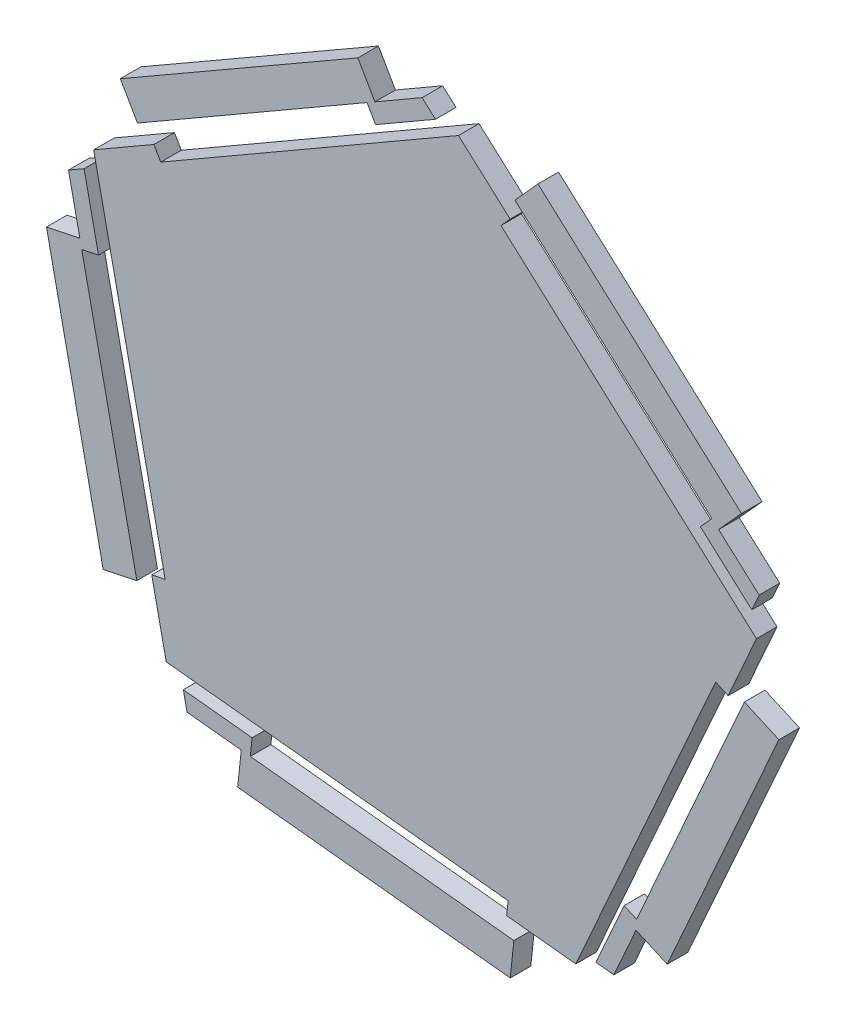
SolidWorks part; units mm, degrees
ref_plane "Front Plane" through (0, 0, 0) normal (0, 0, 1) x (1, 0, 0)
ref_plane "Top Plane" through (0, 0, 0) normal (0, 1, 0) x (1, 0, 0)
ref_plane "Right Plane" through (0, 0, 0) normal (1, 0, 0) x (0, 0, -1)
sketch "Sketch1" plane through (0, 0, 0) normal (0, 0, 1) x (1, 0, 0)
  line L1 (-41.404, -45.8843) -> (30.844, -53.5566)
  line L2 (30.844, -53.5566) -> (60.4667, 12.7845)
  line L3 (60.4667, 12.7845) -> (6.5264, 61.4578)
  line L4 (6.5264, 61.4578) -> (-56.4331, 25.1985)
  line L5 (-56.4331, 25.1985) -> (-41.404, -45.8843)
  circle A0 centre (0, 0) radius 50 construction
extrude "Boss-Extrude1" add sketch "Sketch1" along normal blind 3 contours L4 L5 L1 L2 L3
sketch "Sketch4" plane through (0, 0, 3) normal (0, 0, 1) x (1, 0, 0)
  line L0 (14.0812, -44.2141) -> (14.2946, -42.2255)
  line L1 (49.2224, -0.0815) -> (48.7656, 0.1219)
  line L3 (-39.7738, 28.9981) -> (-6.2904, 48.3298)
  line L4 (-47.56, 19.3386) -> (-49.8378, 18.0301)
  line L5 (-23.3185, -42.797) -> (15.1331, -46.8384)
  line L6 (1.747, 52.9701) -> (-5.1421, 48.9927)
  line L7 (5.2171, 49.1278) -> (5.2906, 49.8199) construction
  line L8 (49.8438, 12.3098) -> (50.9174, 14.7072)
  line L9 (44.0205, 20.9172) -> (15.288, 46.7881)
  line L10 (46.4014, -0.2709) -> (44.5761, 0.5466)
  line L12 (29.7217, -43.8806) -> (32.9573, -36.6135)
  line L22 (-41.404, -45.8843) -> (30.844, -53.5566) construction
  line L23 (14.6082, -51.8324) -> (15.1331, -46.8384)
  line L25 (37.5009, -38.6482) -> (32.9573, -36.6135)
  line L26 (37.5009, -38.6482) -> (30.844, -53.5566)
  line L27 (30.844, -53.5566) -> (14.6082, -51.8324)
  line L28 (-44.7814, -29.9103) -> (-39.8696, -28.8663)
  line L29 (-25.1682, -47.6084) -> (-24.6325, -42.6156)
  line L30 (-25.1682, -47.6084) -> (-41.404, -45.8843)
  line L31 (-41.404, -45.8843) -> (-44.7814, -29.9103)
  line L32 (-37.6988, -27.055) -> (-35.7416, -26.6434)
  line L33 (-42.2846, 33.3468) -> (-39.7738, 28.9981)
  line L34 (-53.0557, 9.2245) -> (-48.1417, 10.258)
  line L35 (-53.0557, 9.2245) -> (-56.4331, 25.1985)
  line L36 (-56.4331, 25.1985) -> (-42.2846, 33.3468)
  line L37 (-37.3804, 27.4932) -> (-36.3841, 25.759)
  line L38 (18.6481, 50.5198) -> (15.288, 46.7881)
  line L39 (-7.6221, 53.3095) -> (-5.1207, 48.9553)
  line L40 (-7.6221, 53.3095) -> (6.5264, 61.4578)
  line L41 (6.5264, 61.4578) -> (18.6481, 50.5198)
  line L42 (14.5964, 44.0467) -> (13.255, 42.5633)
  line L43 (53.8097, -2.1239) -> (49.2224, -0.0815)
  line L44 (48.345, 23.7226) -> (45.0058, 20.03)
  line L45 (48.345, 23.7226) -> (60.4667, 12.7845)
  line L46 (60.4667, 12.7845) -> (53.8097, -2.1239)
  line L50 (-44.7814, -29.9103) -> (-39.8696, -28.8663)
  line L51 (-41.404, -45.8843) -> (-44.7814, -29.9103)
  line L52 (-25.1682, -47.6084) -> (-41.404, -45.8843)
  line L53 (-25.1682, -47.6084) -> (-24.6325, -42.6156)
  line L54 (-24.6325, -42.6156) -> (-32.5518, -41.8105)
  line L56 (-42.2846, 33.3468) -> (-39.7738, 28.9981)
  line L57 (-56.4331, 25.1985) -> (-42.2846, 33.3468)
  line L58 (-53.0557, 9.2245) -> (-56.4331, 25.1985)
  line L59 (-53.0557, 9.2245) -> (-48.1417, 10.258)
  line L60 (-48.1417, 10.258) -> (-49.8232, 18.0385)
  line L62 (18.6481, 50.5198) -> (15.288, 46.7881)
  line L63 (6.5264, 61.4578) -> (18.6481, 50.5198)
  line L64 (-7.6221, 53.3095) -> (6.5264, 61.4578)
  line L65 (-7.6221, 53.3095) -> (-5.1207, 48.9553)
  line L66 (-5.1207, 48.9553) -> (1.7594, 52.9589)
  line L68 (53.8097, -2.1239) -> (49.2224, -0.0815)
  line L69 (60.4667, 12.7845) -> (53.8097, -2.1239)
  line L70 (48.345, 23.7226) -> (60.4667, 12.7845)
  line L71 (48.345, 23.7226) -> (45.0058, 20.03)
  line L73 (33.0398, -35.1989) -> (31.2127, -34.3854)
  line L75 (31.2127, -34.3854) -> (27.1099, -43.6004)
  line L76 (46.4014, -0.2709) -> (50.5296, 9.0011)
  line L78 (33.0398, -35.1989) -> (48.7656, 0.1219)
  line L80 (44.5761, 0.5466) -> (24.175, -45.275)
  line L81 (-23.0572, -40.3107) -> (-33.089, -39.2563)
  line L82 (-33.089, -39.2563) -> (-32.5484, -41.8269)
  line L83 (14.2946, -42.2255) -> (-35.5886, -36.9826)
  line L84 (14.0812, -44.2141) -> (24.175, -45.275)
  line L85 (-37.6988, -27.055) -> (-35.5886, -36.9826)
  line L87 (13.8103, -46.7398) -> (13.8146, -46.6998)
  line L88 (-23.3185, -42.797) -> (-23.0572, -40.3107)
  line L89 (-45.4628, 9.472) -> (-47.56, 19.3386)
  line L90 (-47.9082, 8.9522) -> (-39.8696, -28.8663)
  line L91 (-35.7416, -26.6434) -> (-46.17, 22.4185)
  line L92 (-37.3804, 27.4932) -> (-46.17, 22.4185)
  line L93 (3.6953, 51.2082) -> (1.747, 52.9701)
  line L95 (-40.1846, -27.5777) -> (-40.1453, -27.5695)
  line L96 (-47.9082, 8.9522) -> (-45.4628, 9.472)
  line L97 (-5.0404, 46.1647) -> (3.6953, 51.2082)
  line L98 (14.5964, 44.0467) -> (7.054, 50.838)
  line L99 (-36.3841, 25.759) -> (7.054, 50.838)
  line L104 (-6.2904, 48.3298) -> (-5.0404, 46.1647)
  line L105 (42.3477, 19.0594) -> (49.8438, 12.3098)
  line L107 (13.255, 42.5633) -> (50.5296, 9.0011)
  line L111 (16.3002, 45.9308) -> (16.2733, 45.901)
  line L112 (44.0205, 20.9172) -> (42.3477, 19.0594)
  line L113 (27.1099, -43.6004) -> (29.7217, -43.8806)
  line L114 (-45.7012, 20.4065) -> (-45.7466, 20.4268) construction
  line L121 (-49.8378, 18.0301) -> (-48.1838, 10.2491)
  line L124 (50.9174, 14.7072) -> (45.0058, 20.03)
  line L131 (-23.2663, -42.2997) -> (13.8679, -46.2027) [skipped]
  line L133 (-32.5484, -41.8269) -> (-24.6371, -42.6584)
  line L136 (-47.4191, 9.0562) -> (-39.656, -27.4666) [skipped]
  line L137 (-45.4628, 9.472) -> (-41.5808, -8.7915) [skipped]
  line L139 (-22.2085, 38.5621) -> (-38.3766, 29.2274) [skipped]
  line L140 (-5.0404, 46.1647) -> (-21.2103, 36.829) [skipped]
  line L142 (42.3477, 19.0594) -> (28.4721, 31.553) [skipped]
  line L143 (43.686, 20.5456) -> (29.8119, 33.0379) [skipped]
  arc A2 (-4.752, -44.7484) -> (-4.7038, -44.7535) centre (0, 0) ccw construction
  arc A3 (-4.752, -44.7484) -> (-4.7038, -44.7535) centre (0, 0) ccw construction
  arc A4 (-4.752, -44.7484) -> (-4.7038, -44.7535) centre (0, 0) ccw construction
  arc A5 (-4.752, -44.7484) -> (-4.7038, -44.7535) centre (0, 0) ccw construction
  arc A7 (30.1469, 33.4091) -> (30.1109, 33.4415) centre (0, 0) ccw construction
  arc A8 (30.1469, 33.4091) -> (30.1109, 33.4415) centre (0, 0) ccw construction
  arc A9 (30.1469, 33.4091) -> (30.1109, 33.4415) centre (0, 0) ccw construction
  arc A10 (30.1469, 33.4091) -> (30.1109, 33.4415) centre (0, 0) ccw construction
  arc A11 (30.1469, 33.4091) -> (30.1109, 33.4415) centre (0, 0) ccw construction
  point P18 (0, 0)
  point P65 (0, 0)
  point P90 (0, 0)
  point P156 (0, 0)
  line M1 (60.4667, 12.7845) -> (6.5264, 61.4578)
  line M2 (6.5264, 61.4578) -> (-56.4331, 25.1985)
  line M3 (-56.4331, 25.1985) -> (-41.404, -45.8843)
  line M4 (-41.404, -45.8843) -> (30.844, -53.5566)
  line M5 (30.844, -53.5566) -> (60.4667, 12.7845)
  dimension "D3" = 5
  dimension "D4" = 5
  dimension "D7" = 5
sketch "Sketch2" plane through (0, 0, 3) normal (0, 0, 1) x (1, 0, 0)
  line L0 (1.6748, 1.8561) -> (0, 0) construction
  line L1 (0, 0) -> (20.8319, 18.7092) construction
  line L2 (2.2828, -1.0193) -> (0, 0) construction
  line L3 (14.0812, -44.2141) -> (14.2946, -42.2255) construction
  line L4 (19.5595, 6.8492) -> (25.5253, 6.2092) construction
  line L5 (-1.2477, 2.1664) -> (0, 0) construction
  line L6 (20.8319, 18.7092) -> (25.5253, 6.2092) construction
  line L7 (0, 0) -> (-2.4459, -0.5171) construction
  line L8 (0, 0) -> (-0.264, -2.486) construction
  line L9 (8.9062, 24.7138) -> (19.5595, 6.8492) construction
  line L10 (0, 0) -> (-11.3561, 25.5937) construction
  line L11 (-11.3561, 25.5937) -> (1.9825, 26.1947) construction
  line L12 (-20.7521, 16.1073) -> (-0.4698, 20.7187) construction
  line L13 (-0.4698, 20.7187) -> (1.9825, 26.1947) construction
  line L14 (0, 0) -> (-27.8503, -2.8914) construction
  line L15 (-27.8503, -2.8914) -> (-24.3, 9.98) construction
  line L16 (-21.7317, -14.759) -> (-19.8498, 5.9556) construction
  line L17 (-19.8498, 5.9556) -> (-24.3, 9.98) construction
  line L18 (0, 0) -> (-5.8563, -27.3807) construction
  line L19 (-5.8563, -27.3807) -> (-17.0007, -20.0267) construction
  line L20 (7.3212, -25.2288) -> (-11.7981, -17.0379) construction
  line L21 (-11.7981, -17.0379) -> (-17.0007, -20.0267) construction
  line L22 (0, 0) -> (24.2309, -14.0308) construction
  line L23 (24.2309, -14.0308) -> (13.793, -22.3572) construction
  line L24 (26.2564, -0.8333) -> (12.5582, -16.4857) construction
  line L25 (12.5582, -16.4857) -> (13.793, -22.3572) construction
  circle A6 centre (0, 0) radius 2.5
  circle A7 centre (20.8319, 18.7092) radius 2.5
  circle A12 centre (25.5253, 6.2092) radius 2.5
  circle A13 centre (8.9062, 24.7138) radius 2.5
  circle A22 centre (-11.3561, 25.5937) radius 2.5
  circle A23 centre (1.9825, 26.1947) radius 2.5
  circle A24 centre (-20.7521, 16.1073) radius 2.5
  circle A25 centre (-27.8503, -2.8914) radius 2.5
  circle A26 centre (-24.3, 9.98) radius 2.5
  circle A27 centre (-21.7317, -14.759) radius 2.5
  circle A28 centre (-5.8563, -27.3807) radius 2.5
  circle A29 centre (-17.0007, -20.0267) radius 2.5
  circle A30 centre (7.3212, -25.2288) radius 2.5
  circle A31 centre (24.2309, -14.0308) radius 2.5
  circle A32 centre (13.793, -22.3572) radius 2.5
  circle A33 centre (26.2564, -0.8333) radius 2.5
  point P21 (0, 0)
  point P45 (-0.3503, 0.9716)
  point P50 (0, 0)
  dimension "D1" = 28
  dimension "D2" = 6
  dimension "D3" = 12.5
  dimension "D4" = 5
extrude "Cut-Extrude3" cut sketch "Sketch4" against normal blind 10 contours L133 L82 L81 L88 L5 L23 L25 L12 L113 L75 L73 L78 L1 L43 L44 L124 L8 L105 L112 L9 L38 L39 L6 L93 L97 L104 L3 L33 L34 L121 L4 L89 L96 L90 L28 M4 M5 M1 M2 M3
